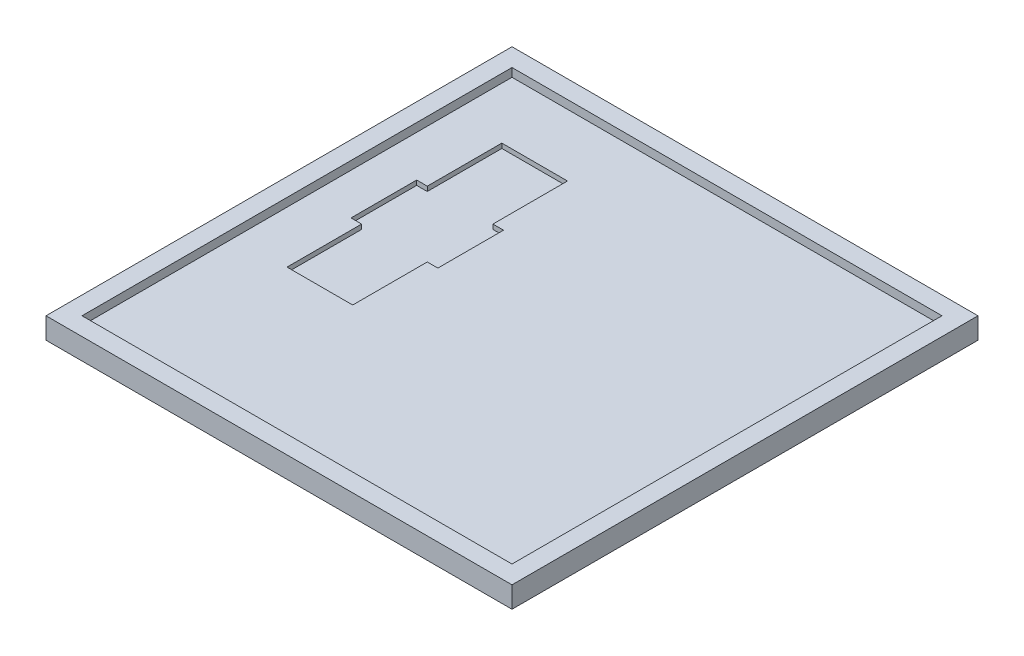
SolidWorks part; units mm, degrees
ref_plane "Front Plane" through (0, 0, 0) normal (0, 0, 1) x (1, 0, 0)
ref_plane "Top Plane" through (0, 0, 0) normal (0, 1, 0) x (1, 0, 0)
ref_plane "Right Plane" through (0, 0, 0) normal (1, 0, 0) x (0, 0, -1)
sketch "Sketch1" plane through (0, 0, 0) normal (0, 1, 0) x (1, 0, 0)
  line L1 (-68.863, 38.3493) -> (41.137, 38.3493)
  line L2 (-68.863, 38.3493) -> (-68.863, -71.6507)
  line L3 (-68.863, -71.6507) -> (41.137, -71.6507)
  line L4 (41.137, 38.3493) -> (41.137, -71.6507)
  dimension "D1" = 110
  dimension "D2" = 110
extrude "Boss-Extrude1" add sketch "Sketch1" along normal blind 5
sketch "Sketch2" plane through (0, 5, 0) normal (0, 1, 0) x (1, 0, 0)
  line L0 (41.137, 38.3493) -> (-68.863, 38.3493) construction
  line L1 (-64.613, 34.0993) -> (36.887, 34.0993)
  line L2 (-64.613, 34.0993) -> (-64.613, -67.4007)
  line L3 (-64.613, -67.4007) -> (36.887, -67.4007)
  line L4 (36.887, 34.0993) -> (36.887, -67.4007)
  line L5 (41.137, -71.6507) -> (41.137, 38.3493) construction
  point P4 (-13.863, 34.0993)
  point P7 (-13.863, 38.3493)
  point P8 (36.887, -16.6507)
  point P11 (41.137, -16.6507)
  dimension "D1" = 101.5
  dimension "D2" = 101.5
extrude "Cut-Extrude1" cut sketch "Sketch2" against normal blind 2
sketch "Sketch3" plane through (0, 3, 0) normal (0, 1, 0) x (1, 0, 0)
  line L0 (-44.613, 14.0993) -> (-44.613, -25.9007) construction
  line L1 (-64.613, 34.0993) -> (-64.613, -67.4007) construction
  line L2 (36.887, 34.0993) -> (-64.613, 34.0993) construction
  line L3 (-34.363, 1.8493) -> (-36.863, 1.8493)
  line L4 (-34.363, 1.8493) -> (-34.363, -13.6507)
  line L5 (-34.363, -13.6507) -> (-36.863, -13.6507)
  line L6 (-54.863, 1.8493) -> (-54.863, -13.6507)
  line L7 (-54.863, 1.8493) -> (-34.363, -13.6507) construction
  line L8 (-36.863, 19.4493) -> (-52.363, -31.2507) construction
  line L9 (-52.363, 19.4493) -> (-36.863, 19.4493)
  line L10 (-52.363, 19.4493) -> (-52.363, 1.8493)
  line L11 (-52.363, -31.2507) -> (-36.863, -31.2507)
  line L12 (-36.863, 19.4493) -> (-36.863, 1.8493)
  line L13 (-52.363, 1.8493) -> (-54.863, 1.8493)
  line L14 (-36.863, -13.6507) -> (-36.863, -31.2507)
  line L16 (-52.363, -13.6507) -> (-54.863, -13.6507)
  line L17 (-52.363, -13.6507) -> (-52.363, -31.2507)
  point P10 (-44.613, -5.9007)
  point P11 (-44.613, -5.9007)
  point P16 (-44.613, -5.9007)
  dimension "D1" = 20
  dimension "D2" = 20.5
  dimension "D3" = 15.5
  dimension "D4" = 20
  dimension "D5" = 40
  dimension "D6" = 15.5
  dimension "D7" = 50.7
extrude "Cut-Extrude2" cut sketch "Sketch3" against normal blind 1.1
